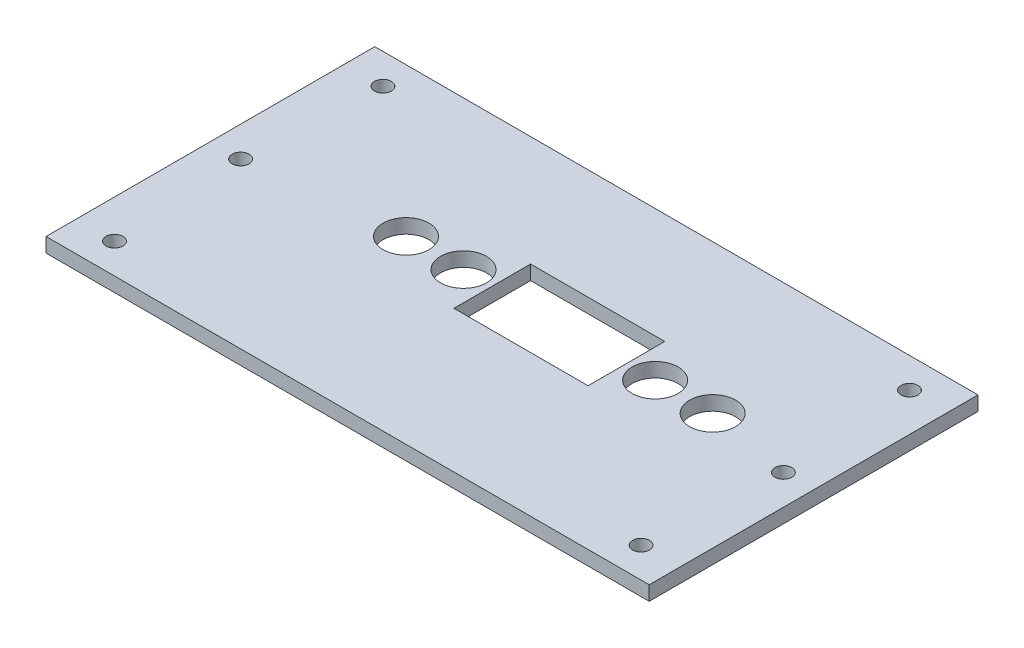
SolidWorks part; units mm, degrees
material "Acrylic (Medium-high impact)"
ref_plane "Front Plane" through (0, 0, 0) normal (0, 0, 1) x (1, 0, 0)
ref_plane "Top Plane" through (0, 0, 0) normal (0, 1, 0) x (1, 0, 0)
ref_plane "Right Plane" through (0, 0, 0) normal (1, 0, 0) x (0, 0, -1)
sketch "Sketch1" plane through (0, 0, 0) normal (0, 1, 0) x (1, 0, 0)
  line L0 (-50.8, 0) -> (50.8, 0) construction
  line L1 (-22.225, 12.7) -> (22.225, 12.7)
  line L2 (-22.225, 12.7) -> (-22.225, -12.7)
  line L3 (-22.225, -12.7) -> (22.225, -12.7)
  line L4 (22.225, 12.7) -> (22.225, -12.7)
  line L5 (0, 12.7) -> (0, -12.7) construction
  line L7 (-110.4265, 49.276) -> (89.4715, 49.276)
  line L8 (-110.4265, 49.276) -> (-110.4265, -59.69)
  line L9 (-110.4265, -59.69) -> (89.4715, -59.69)
  line L10 (89.4715, 49.276) -> (89.4715, -59.69)
  circle A0 centre (-50.8, 0) radius 7.62
  circle A1 centre (-31.75, 0) radius 7.62
  circle A2 centre (31.75, 0) radius 7.62
  circle A3 centre (50.8, 0) radius 7.62
  circle A4 centre (-97.7265, 39.2684) radius 2.794
  circle A5 centre (76.7715, 39.2684) radius 2.794
  circle A6 centre (79.4639, -5.207) radius 2.794
  circle A7 centre (76.7715, -49.6824) radius 2.794
  circle A8 centre (-97.7265, -49.6824) radius 2.794
  circle A9 centre (-100.4189, -5.207) radius 2.794
  dimension "D1" = 15.24
  dimension "D2" = 15.24
  dimension "D3" = 15.24
  dimension "D4" = 15.24
  dimension "D16" = 5.588
  dimension "D17" = 5.588
  dimension "D18" = 5.588
  dimension "D19" = 5.588
  dimension "D20" = 5.588
  dimension "D21" = 5.588
  dimension "D5" = 19.05
  dimension "D6" = 19.05
  dimension "D7" = 63.5
  dimension "D8" = 31.75
  dimension "D9" = 44.45
  dimension "D10" = 25.4
  dimension "D11" = 12.7
  dimension "D12" = 108.966
  dimension "D13" = 59.6265
  dimension "D14" = 59.69
  dimension "D15" = 38.6715
  dimension "D22" = 10.0076
  dimension "D23" = 12.7
  dimension "D24" = 10.0076
  dimension "D25" = 12.7
  dimension "D26" = 10.0076
  dimension "D27" = 54.483
  dimension "D28" = 10.0076
  dimension "D29" = 10.0076
  dimension "D30" = 12.7
  dimension "D31" = 12.7
  dimension "D32" = 10.0076
  dimension "D33" = 54.483
extrude "Boss-Extrude1" add sketch "Sketch1" along normal blind 4.7625
